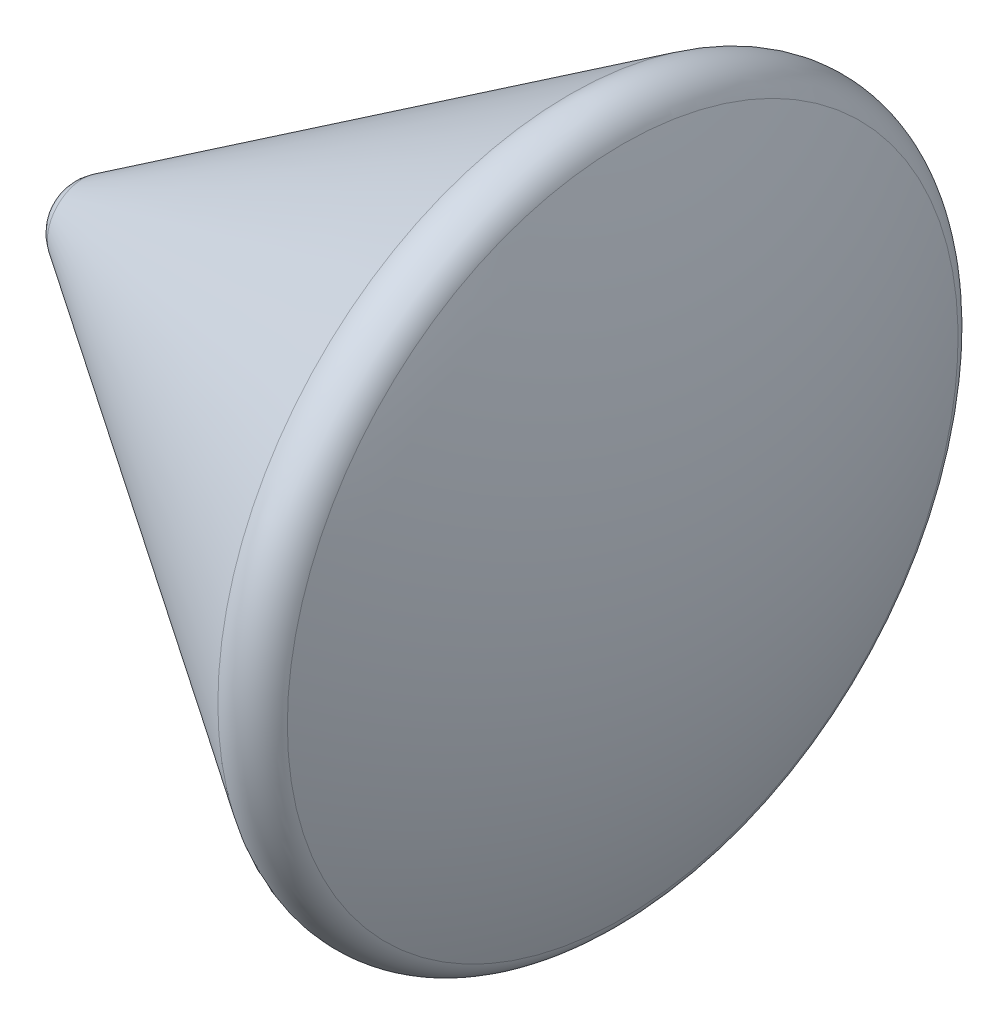
SolidWorks part; units mm, degrees
ref_plane "Piano frontale" through (0, 0, 0) normal (0, 0, 1) x (1, 0, 0)
ref_plane "Piano superiore" through (0, 0, 0) normal (0, 1, 0) x (1, 0, 0)
ref_plane "Piano destro" through (0, 0, 0) normal (1, 0, 0) x (0, 0, -1)
sketch "Schizzo1" plane through (0, 0, 0) normal (0, 0, 1) x (1, 0, 0)
  line L0 (105.1884, 193.7329) -> (2738.3446, 1903.7245)
  line L1 (2845.0938, 1935.3451) -> (2845.0938, 0) construction
  line L2 (0, 0) -> (3391, 0)
  arc A0 (2738.3446, 1903.7245) -> (3025.8467, 1815.1369) centre (2845.0938, 1739.3451) cw
  arc A1 (3025.8467, 1815.1369) -> (3391, 0) centre (-1303, 0) cw
  arc A2 (105.1884, 193.7329) -> (0, 0) centre (231, 0) ccw
  point P8 (2550, 0)
  dimension "D1" = 231
  dimension "D2" = 196
  dimension "D3" = 4694
  dimension "D4" = 33
  dimension "D5" = 3391
  dimension "D6" = 1935.3451
  dimension "D7" = 2550
revolve "Rivoluzione1" add sketch "Schizzo1" angle 360 about L2
